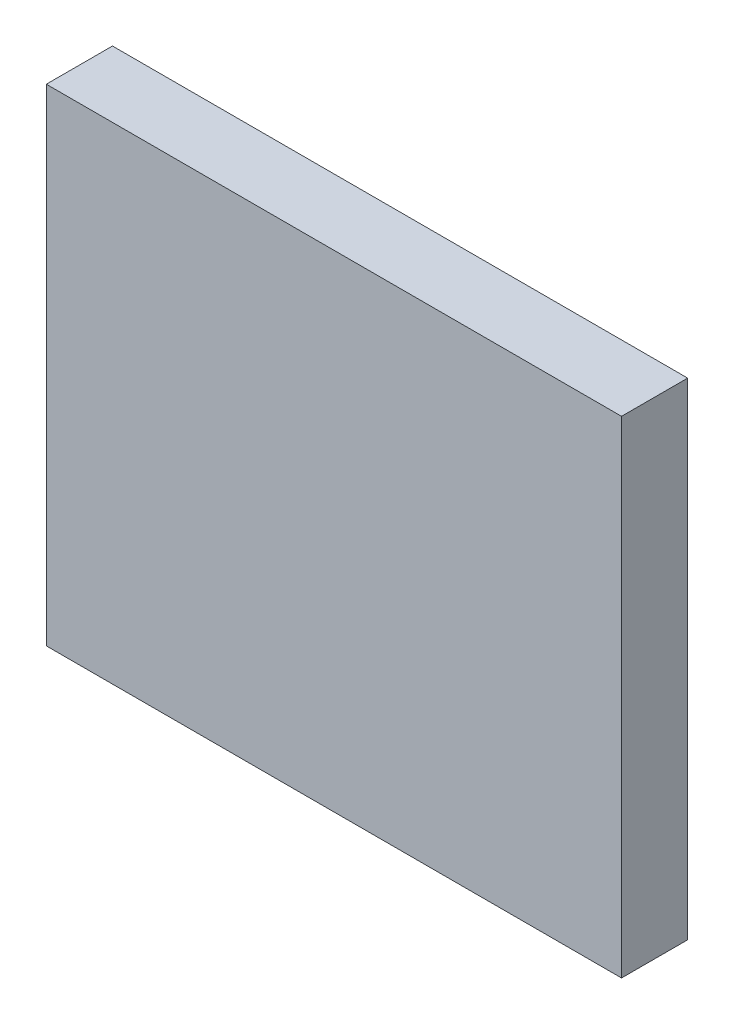
SolidWorks part; units mm, degrees
ref_plane "Front Plane" through (0, 0, 0) normal (0, 0, 1) x (1, 0, 0)
ref_plane "Top Plane" through (0, 0, 0) normal (0, 1, 0) x (1, 0, 0)
ref_plane "Right Plane" through (0, 0, 0) normal (1, 0, 0) x (0, 0, -1)
sketch "Sketch1" plane through (0, 0, 0) normal (0, 0, 1) x (1, 0, 0)
  line L0 (-4.3472, -3.6025) -> (4.3472, -3.6025)
  line L1 (4.3472, -3.6025) -> (4.3472, 3.75)
  line L2 (4.3472, 3.75) -> (-4.3472, 3.75)
  line L3 (-4.3472, 3.75) -> (-4.3472, -3.6025)
extrude "Boss-Extrude1" add sketch "Sketch1" along normal blind 1 from offset 0
